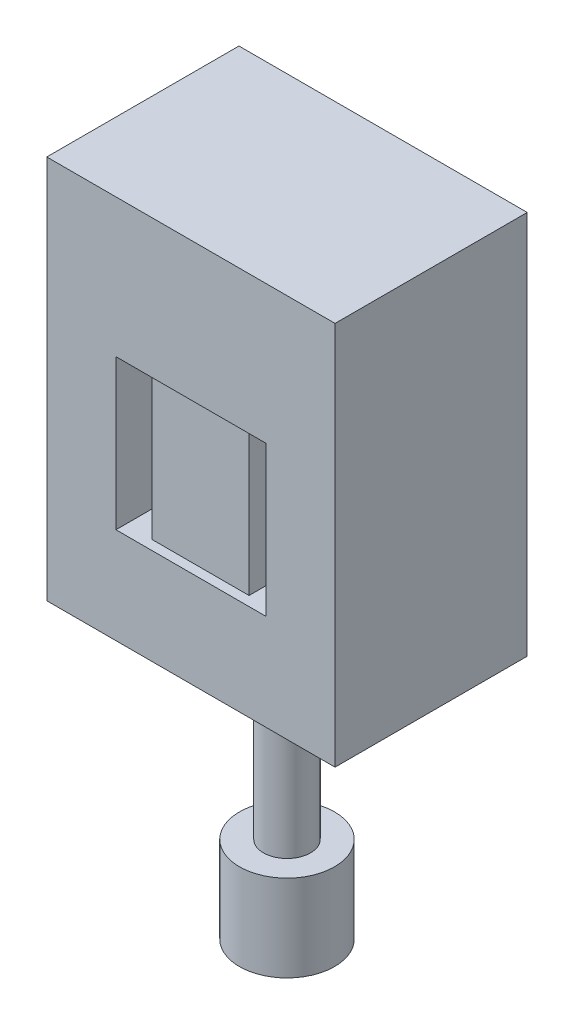
SolidWorks part; units mm, degrees
ref_plane "前视基准面" through (0, 0, 0) normal (0, 0, 1) x (1, 0, 0)
ref_plane "上视基准面" through (0, 0, 0) normal (0, 1, 0) x (1, 0, 0)
ref_plane "右视基准面" through (0, 0, 0) normal (1, 0, 0) x (0, 0, -1)
other "Configuration Table"
sketch "草图1" plane through (0, 0, 0) normal (0, 1, 0) x (1, 0, 0)
  line L1 (-15, -10) -> (15, -10)
  line L2 (-15, -10) -> (-15, 10)
  line L3 (-15, 10) -> (15, 10)
  line L4 (15, -10) -> (15, 10)
  line L5 (-15, -10) -> (15, 10) construction
  line L6 (-15, 10) -> (15, -10) construction
  point P0 (0, 0)
  point P6 (15, 4.1317)
  dimension "D1" = 20
  dimension "D2" = 30
extrude "凸台-拉伸1" add sketch "草图1" along normal blind 40
sketch "草图2" plane through (0, 0, 0) normal (0, -1, 0) x (1, 0, 0)
  circle A0 centre (0, 0) radius 2.45
  dimension "D1" = 4.9
extrude "凸台-拉伸2" add sketch "草图2" along normal blind 19
sketch "草图3" plane through (0, -19, 0) normal (0, -1, 0) x (1, 0, 0)
  circle A0 centre (0, 0) radius 4.95
  dimension "D1" = 9.9
extrude "凸台-拉伸3" add sketch "草图3" along normal blind 9
sketch "草图4" plane through (0, 0, 10) normal (0, 0, 1) x (1, 0, 0)
  line L1 (-7.8, 10) -> (7.8, 10)
  line L2 (-7.8, 10) -> (-7.8, 25.6)
  line L3 (-7.8, 25.6) -> (7.8, 25.6)
  line L4 (7.8, 10) -> (7.8, 25.6)
  line L5 (-7.8, 10) -> (7.8, 25.6) construction
  line L6 (-7.8, 25.6) -> (7.8, 10) construction
  point P0 (0, 17.8)
  dimension "D1" = 15.6
  dimension "D2" = 15.6
  dimension "D3" = 10
extrude "切除-拉伸1" cut sketch "草图4" against normal blind 1
sketch "草图5" plane through (0, 0, 9) normal (0, 0, 1) x (1, 0, 0)
  line L0 (-7.8, 10) -> (7.8, 10) construction
  line L1 (-7.8, 25.6) -> (-5.05, 25.6)
  line L2 (-7.8, 25.6) -> (-7.8, 10)
  line L3 (-7.8, 10) -> (-5.05, 10)
  line L4 (-5.05, 25.6) -> (-5.05, 10)
  line L5 (-7.8, 10) -> (7.8, 10) construction
  line L6 (7.8, 25.6) -> (5.05, 25.6)
  line L7 (7.8, 25.6) -> (7.8, 10)
  line L8 (7.8, 10) -> (5.05, 10)
  line L9 (5.05, 25.6) -> (5.05, 10)
  dimension "D1" = 10.1
extrude "切除-拉伸2" cut sketch "草图5" against normal blind 3
fillet "圆角1" radius 3 1 edges at (0, 0, -2.45)
